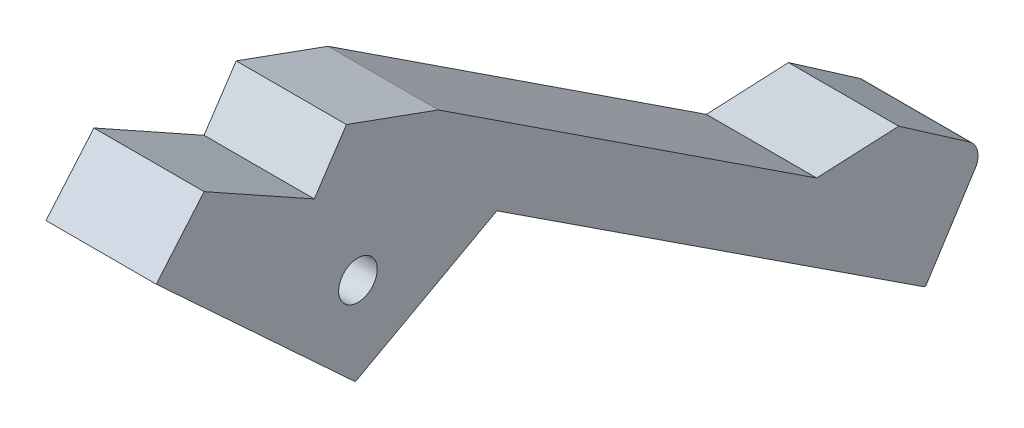
SolidWorks part; units mm, degrees
ref_plane "정면" through (0, 0, 0) normal (0, 0, 1) x (1, 0, 0)
ref_plane "윗면" through (0, 0, 0) normal (0, 1, 0) x (1, 0, 0)
ref_plane "우측면" through (0, 0, 0) normal (1, 0, 0) x (0, 0, -1)
sketch "스케치1" plane through (0, 0, 0) normal (1, 0, 0) x (0, 0, -1)
  line L0 (-1.2473, 15.2901) -> (-4.7472, 10.0276)
  line L1 (49.9252, -15.3349) -> (58.8608, -14.9204)
  line L2 (58.8608, -14.9204) -> (66.5706, -20.2596)
  line L3 (67.3179, -22.8463) -> (61.806, -31.4452)
  line L4 (61.6328, -31.4452) -> (15.1257, -1.0289)
  line L5 (8.7468, 11.6712) -> (49.9252, -15.3349)
  line L7 (61.806, -31.4452) -> (61.6328, -31.4452)
  line L8 (15.1257, -1.0289) -> (-0.2818, -9.4351)
  line L9 (-0.2818, -9.4351) -> (-21.9484, 10.5905)
  line L11 (-1.2473, 15.2901) -> (8.7468, 11.6712)
  line L15 (-21.9484, 10.5905) -> (-16.7379, 16.712)
  line L17 (-16.7379, 16.712) -> (-4.7472, 10.0276)
  circle A0 centre (0, 0) radius 2.1
  arc A1 (66.5706, -20.2596) -> (67.3179, -22.8463) centre (65.3574, -22.0114) cw
  dimension "D1" = 4.2
extrude "보스-돌출1" add sketch "스케치1" along normal mid plane 12
